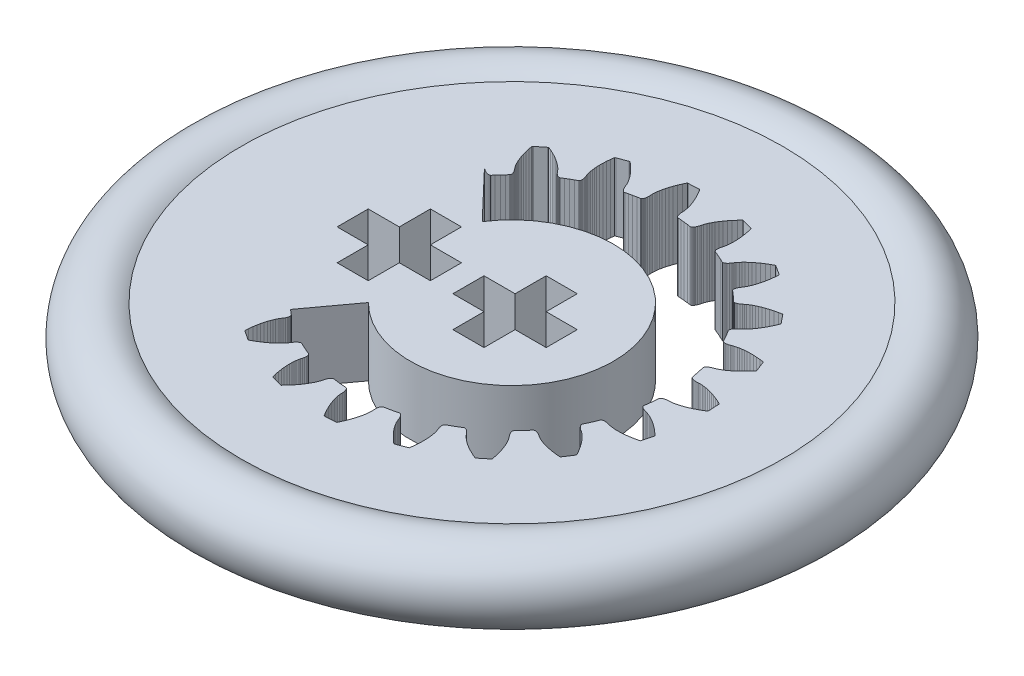
SolidWorks part; units mm, degrees
ref_plane "Front Plane" through (0, 0, 0) normal (0, 0, 1) x (1, 0, 0)
ref_plane "Top Plane" through (0, 0, 0) normal (0, 1, 0) x (1, 0, 0)
ref_plane "Right Plane" through (0, 0, 0) normal (1, 0, 0) x (0, 0, -1)
sketch "Sketch1" plane through (0, 0, 0) normal (0, 0, 1) x (1, 0, 0)
  line L0 (0, 0) -> (-11.938, 0)
  line L1 (-11.0639, 2.7724) -> (0, 2.7724)
  line L2 (0, 2.7724) -> (0, 0)
  line L3 (-11.938, 1.524) -> (-11.938, 3.048) construction
  line L4 (-11.938, 1.524) -> (-11.0639, 2.7724) construction
  arc A0 (-11.938, 0) -> (-11.0639, 2.7724) centre (-11.938, 1.524) cw
  dimension "D1" = 1.524
  dimension ".94/2" = 11.938
  dimension "D3" = 35
revolve "Revolve1" add sketch "Sketch1" angle 360 about L2
sketch "Sketch2" plane through (0, 2.7724, 0) normal (0, 1, 0) x (1, 0, 0)
  line L0 (-2.9392, -2.9262) -> (-4.2846, -4.7586)
  line L1 (-3.4764, 2.2619) -> (-5.3211, 4.1958)
  line L684 (7.7125, 0.0884) -> (7.5777, 0.013)
  line L685 (7.5777, 0.013) -> (7.4507, -0.0512)
  line L686 (7.4507, -0.0512) -> (7.332, -0.1049)
  line L687 (7.332, -0.1049) -> (7.2218, -0.1493)
  line L688 (7.2218, -0.1493) -> (7.1202, -0.1856)
  line L689 (7.1202, -0.1856) -> (7.0292, -0.2135)
  line L690 (7.0292, -0.2135) -> (6.9484, -0.235)
  line L691 (6.9484, -0.235) -> (6.8784, -0.2501)
  line L692 (6.8784, -0.2501) -> (6.7713, -0.2671)
  line L693 (6.7713, -0.2671) -> (6.7097, -0.2717)
  line L694 (6.7097, -0.2717) -> (6.6537, -0.2735)
  line L695 (6.6537, -0.2735) -> (6.5775, -0.2818)
  line L696 (6.5775, -0.2818) -> (6.5137, -0.2964)
  line L697 (6.5137, -0.2964) -> (6.4868, -0.3059)
  line L698 (6.4868, -0.3059) -> (6.4632, -0.3168)
  line L699 (6.4632, -0.3168) -> (6.4425, -0.3284)
  line L700 (6.4425, -0.3284) -> (6.4255, -0.341)
  line L701 (6.4255, -0.341) -> (6.4115, -0.354)
  line L702 (6.4115, -0.354) -> (6.4013, -0.3684)
  line L703 (6.4013, -0.3684) -> (6.3942, -0.383)
  line L704 (6.3942, -0.383) -> (6.3904, -0.4019)
  line L705 (6.3904, -0.4019) -> (6.3821, -0.5191)
  line L706 (6.3821, -0.5191) -> (6.3678, -0.6695)
  line L707 (6.3678, -0.6695) -> (6.3504, -0.8194)
  line L708 (6.3504, -0.8194) -> (6.3343, -0.9361)
  line L709 (6.3343, -0.9361) -> (6.334, -0.9552)
  line L710 (6.334, -0.9552) -> (6.3379, -0.9706)
  line L711 (6.3379, -0.9706) -> (6.3451, -0.9869)
  line L712 (6.3451, -0.9869) -> (6.356, -1.0026)
  line L713 (6.356, -1.0026) -> (6.37, -1.0187)
  line L714 (6.37, -1.0187) -> (6.3875, -1.0342)
  line L715 (6.3875, -1.0342) -> (6.4086, -1.0495)
  line L716 (6.4086, -1.0495) -> (6.433, -1.0644)
  line L717 (6.433, -1.0644) -> (6.4922, -1.0923)
  line L718 (6.4922, -1.0923) -> (6.5653, -1.1162)
  line L719 (6.5653, -1.1162) -> (6.6196, -1.1296)
  line L720 (6.6196, -1.1296) -> (6.6786, -1.1466)
  line L721 (6.6786, -1.1466) -> (6.7801, -1.1854)
  line L722 (6.7801, -1.1854) -> (6.8453, -1.2149)
  line L723 (6.8453, -1.2149) -> (6.9202, -1.2529)
  line L724 (6.9202, -1.2529) -> (7.0032, -1.2991)
  line L725 (7.0032, -1.2991) -> (7.0951, -1.3557)
  line L726 (7.0951, -1.3557) -> (7.1936, -1.422)
  line L727 (7.1936, -1.422) -> (7.2987, -1.4993)
  line L728 (7.2987, -1.4993) -> (7.4094, -1.5885)
  line L729 (7.4094, -1.5885) -> (7.5257, -1.6899)
  line L730 (7.5257, -1.6899) -> (7.6352, -1.794)
  line L731 (7.6352, -1.794) -> (7.6257, -1.8334)
  line L732 (7.6257, -1.8334) -> (7.5208, -2.2251)
  line L733 (7.5208, -2.2251) -> (7.5092, -2.2644)
  line L734 (7.5092, -2.2644) -> (7.3624, -2.2993)
  line L735 (7.3624, -2.2993) -> (7.2109, -2.3294)
  line L736 (7.2109, -2.3294) -> (7.0705, -2.3509)
  line L737 (7.0705, -2.3509) -> (6.9408, -2.3657)
  line L738 (6.9408, -2.3657) -> (6.8223, -2.3739)
  line L739 (6.8223, -2.3739) -> (6.7145, -2.3766)
  line L740 (6.7145, -2.3766) -> (6.6194, -2.3755)
  line L741 (6.6194, -2.3755) -> (6.5356, -2.3706)
  line L742 (6.5356, -2.3706) -> (6.4644, -2.3635)
  line L743 (6.4644, -2.3635) -> (6.3571, -2.3464)
  line L744 (6.3571, -2.3464) -> (6.2975, -2.3319)
  line L745 (6.2975, -2.3319) -> (6.2437, -2.3163)
  line L746 (6.2437, -2.3163) -> (6.1684, -2.3006)
  line L747 (6.1684, -2.3006) -> (6.1033, -2.2947)
  line L748 (6.1033, -2.2947) -> (6.0747, -2.2954)
  line L749 (6.0747, -2.2954) -> (6.0488, -2.2981)
  line L750 (6.0488, -2.2981) -> (6.0259, -2.3031)
  line L751 (6.0259, -2.3031) -> (6.0058, -2.3097)
  line L752 (6.0058, -2.3097) -> (5.9883, -2.3182)
  line L753 (5.9883, -2.3182) -> (5.9741, -2.3284)
  line L754 (5.9741, -2.3284) -> (5.9629, -2.3402)
  line L755 (5.9629, -2.3402) -> (5.9536, -2.3568)
  line L756 (5.9536, -2.3568) -> (5.9092, -2.466)
  line L757 (5.9092, -2.466) -> (5.8493, -2.6045)
  line L758 (5.8493, -2.6045) -> (5.7866, -2.7415)
  line L759 (5.7866, -2.7415) -> (5.735, -2.8476)
  line L760 (5.735, -2.8476) -> (5.729, -2.8659)
  line L761 (5.729, -2.8659) -> (5.7278, -2.8819)
  line L762 (5.7278, -2.8819) -> (5.7295, -2.8992)
  line L763 (5.7295, -2.8992) -> (5.735, -2.9178)
  line L764 (5.735, -2.9178) -> (5.7434, -2.9373)
  line L765 (5.7434, -2.9373) -> (5.7555, -2.9577)
  line L766 (5.7555, -2.9577) -> (5.7707, -2.9785)
  line L767 (5.7707, -2.9785) -> (5.7892, -3.0003)
  line L768 (5.7892, -3.0003) -> (5.8371, -3.0451)
  line L769 (5.8371, -3.0451) -> (5.8989, -3.0904)
  line L770 (5.8989, -3.0904) -> (5.9465, -3.1199)
  line L771 (5.9465, -3.1199) -> (5.9976, -3.1544)
  line L772 (5.9976, -3.1544) -> (6.0819, -3.2225)
  line L773 (6.0819, -3.2225) -> (6.1349, -3.2711)
  line L774 (6.1349, -3.2711) -> (6.1942, -3.3297)
  line L775 (6.1942, -3.3297) -> (6.259, -3.3998)
  line L776 (6.259, -3.3998) -> (6.3289, -3.4816)
  line L777 (6.3289, -3.4816) -> (6.4021, -3.5751)
  line L778 (6.4021, -3.5751) -> (6.478, -3.6814)
  line L779 (6.478, -3.6814) -> (6.5559, -3.8005)
  line L780 (6.5559, -3.8005) -> (6.6351, -3.9328)
  line L781 (6.6351, -3.9328) -> (6.707, -4.0655)
  line L782 (6.707, -4.0655) -> (6.6857, -4.1001)
  line L783 (6.6857, -4.1001) -> (6.4647, -4.4404)
  line L784 (6.4647, -4.4404) -> (6.4417, -4.4738)
  line L785 (6.4417, -4.4738) -> (6.2915, -4.4619)
  line L786 (6.2915, -4.4619) -> (6.1382, -4.4436)
  line L787 (6.1382, -4.4436) -> (5.9978, -4.4207)
  line L788 (5.9978, -4.4207) -> (5.8699, -4.3944)
  line L789 (5.8699, -4.3944) -> (5.7548, -4.366)
  line L790 (5.7548, -4.366) -> (5.6515, -4.3355)
  line L791 (5.6515, -4.3355) -> (5.5612, -4.3045)
  line L792 (5.5612, -4.3045) -> (5.4834, -4.2745)
  line L793 (5.4834, -4.2745) -> (5.4176, -4.2457)
  line L794 (5.4176, -4.2457) -> (5.3209, -4.1962)
  line L795 (5.3209, -4.1962) -> (5.2685, -4.1638)
  line L796 (5.2685, -4.1638) -> (5.2223, -4.1322)
  line L797 (5.2223, -4.1322) -> (5.1558, -4.094)
  line L798 (5.1558, -4.094) -> (5.0955, -4.0687)
  line L799 (5.0955, -4.0687) -> (5.0682, -4.0606)
  line L800 (5.0682, -4.0606) -> (5.0428, -4.055)
  line L801 (5.0428, -4.055) -> (5.0192, -4.0522)
  line L802 (5.0192, -4.0522) -> (4.998, -4.0526)
  line L803 (4.998, -4.0526) -> (4.9788, -4.0554)
  line L804 (4.9788, -4.0554) -> (4.9623, -4.0606)
  line L805 (4.9623, -4.0606) -> (4.9481, -4.0684)
  line L806 (4.9481, -4.0684) -> (4.9339, -4.0813)
  line L807 (4.9339, -4.0813) -> (4.8579, -4.1712)
  line L808 (4.8579, -4.1712) -> (4.7583, -4.2847)
  line L809 (4.7583, -4.2847) -> (4.6559, -4.3955)
  line L810 (4.6559, -4.3955) -> (4.5745, -4.4803)
  line L811 (4.5745, -4.4803) -> (4.5631, -4.4961)
  line L812 (4.5631, -4.4961) -> (4.5568, -4.5108)
  line L813 (4.5568, -4.5108) -> (4.5534, -4.5278)
  line L814 (4.5534, -4.5278) -> (4.5526, -4.5472)
  line L815 (4.5526, -4.5472) -> (4.5545, -4.5685)
  line L816 (4.5545, -4.5685) -> (4.5596, -4.5914)
  line L817 (4.5596, -4.5914) -> (4.5678, -4.616)
  line L818 (4.5678, -4.616) -> (4.579, -4.6425)
  line L819 (4.579, -4.6425) -> (4.6104, -4.6997)
  line L820 (4.6104, -4.6997) -> (4.6552, -4.762)
  line L821 (4.6552, -4.762) -> (4.6914, -4.8045)
  line L822 (4.6914, -4.8045) -> (4.729, -4.8533)
  line L823 (4.729, -4.8533) -> (4.7882, -4.9442)
  line L824 (4.7882, -4.9442) -> (4.8239, -5.0066)
  line L825 (4.8239, -5.0066) -> (4.8621, -5.0811)
  line L826 (4.8621, -5.0811) -> (4.902, -5.1677)
  line L827 (4.902, -5.1677) -> (4.9433, -5.267)
  line L828 (4.9433, -5.267) -> (4.9838, -5.3786)
  line L829 (4.9838, -5.3786) -> (5.0235, -5.503)
  line L830 (5.0235, -5.503) -> (5.0606, -5.6404)
  line L831 (5.0606, -5.6404) -> (5.095, -5.791)
  line L832 (5.095, -5.791) -> (5.1228, -5.9391)
  line L833 (5.1228, -5.9391) -> (5.0917, -5.9655)
  line L834 (5.0917, -5.9655) -> (4.7764, -6.221)
  line L835 (4.7764, -6.221) -> (4.7442, -6.2455)
  line L836 (4.7442, -6.2455) -> (4.6048, -6.1878)
  line L837 (4.6048, -6.1878) -> (4.4648, -6.1231)
  line L838 (4.4648, -6.1231) -> (4.3379, -6.058)
  line L839 (4.3379, -6.058) -> (4.2246, -5.9932)
  line L840 (4.2246, -5.9932) -> (4.1241, -5.9304)
  line L841 (4.1241, -5.9304) -> (4.0352, -5.8698)
  line L842 (4.0352, -5.8698) -> (3.9587, -5.8125)
  line L843 (3.9587, -5.8125) -> (3.8941, -5.7597)
  line L844 (3.8941, -5.7597) -> (3.8403, -5.7117)
  line L845 (3.8403, -5.7117) -> (3.7639, -5.6349)
  line L846 (3.7639, -5.6349) -> (3.724, -5.5883)
  line L847 (3.724, -5.5883) -> (3.6899, -5.544)
  line L848 (3.6899, -5.544) -> (3.6381, -5.487)
  line L849 (3.6381, -5.487) -> (3.5889, -5.4442)
  line L850 (3.5889, -5.4442) -> (3.5652, -5.4279)
  line L851 (3.5652, -5.4279) -> (3.5429, -5.4147)
  line L852 (3.5429, -5.4147) -> (3.5214, -5.4053)
  line L853 (3.5214, -5.4053) -> (3.5011, -5.3987)
  line L854 (3.5011, -5.3987) -> (3.482, -5.3956)
  line L855 (3.482, -5.3956) -> (3.4645, -5.3953)
  line L856 (3.4645, -5.3953) -> (3.4486, -5.3982)
  line L857 (3.4486, -5.3982) -> (3.4312, -5.4063)
  line L858 (3.4312, -5.4063) -> (3.3311, -5.4682)
  line L859 (3.3311, -5.4682) -> (3.2014, -5.5453)
  line L860 (3.2014, -5.5453) -> (3.0699, -5.6191)
  line L861 (3.0699, -5.6191) -> (2.9662, -5.6748)
  line L862 (2.9662, -5.6748) -> (2.9504, -5.6858)
  line L863 (2.9504, -5.6858) -> (2.94, -5.6981)
  line L864 (2.94, -5.6981) -> (2.9314, -5.7134)
  line L865 (2.9314, -5.7134) -> (2.9247, -5.7316)
  line L866 (2.9247, -5.7316) -> (2.9202, -5.7524)
  line L867 (2.9202, -5.7524) -> (2.9176, -5.7757)
  line L868 (2.9176, -5.7757) -> (2.9178, -5.8017)
  line L869 (2.9178, -5.8017) -> (2.9202, -5.8303)
  line L870 (2.9202, -5.8303) -> (2.9326, -5.8943)
  line L871 (2.9326, -5.8943) -> (2.956, -5.9677)
  line L872 (2.956, -5.9677) -> (2.9774, -6.0194)
  line L873 (2.9774, -6.0194) -> (2.9978, -6.0772)
  line L874 (2.9978, -6.0772) -> (3.0262, -6.1818)
  line L875 (3.0262, -6.1818) -> (3.0407, -6.2524)
  line L876 (3.0407, -6.2524) -> (3.0542, -6.3347)
  line L877 (3.0542, -6.3347) -> (3.0656, -6.4297)
  line L878 (3.0656, -6.4297) -> (3.0736, -6.5369)
  line L879 (3.0736, -6.5369) -> (3.0778, -6.6554)
  line L880 (3.0778, -6.6554) -> (3.0772, -6.7859)
  line L881 (3.0772, -6.7859) -> (3.0702, -6.9282)
  line L882 (3.0702, -6.9282) -> (3.0562, -7.0819)
  line L883 (3.0562, -7.0819) -> (3.0364, -7.2316)
  line L884 (3.0364, -7.2316) -> (2.9991, -7.2471)
  line L885 (2.9991, -7.2471) -> (2.6203, -7.3925)
  line L886 (2.6203, -7.3925) -> (2.5818, -7.4061)
  line L887 (2.5818, -7.4061) -> (2.4675, -7.308)
  line L888 (2.4675, -7.308) -> (2.3542, -7.203)
  line L889 (2.3542, -7.203) -> (2.2538, -7.1021)
  line L890 (2.2538, -7.1021) -> (2.1659, -7.0055)
  line L891 (2.1659, -7.0055) -> (2.0895, -6.9147)
  line L892 (2.0895, -6.9147) -> (2.0241, -6.8293)
  line L893 (2.0241, -6.8293) -> (1.9691, -6.7514)
  line L894 (1.9691, -6.7514) -> (1.9237, -6.6809)
  line L895 (1.9237, -6.6809) -> (1.8875, -6.6189)
  line L896 (1.8875, -6.6189) -> (1.8384, -6.5223)
  line L897 (1.8384, -6.5223) -> (1.8149, -6.4652)
  line L898 (1.8149, -6.4652) -> (1.7962, -6.4127)
  line L899 (1.7962, -6.4127) -> (1.7646, -6.3427)
  line L900 (1.7646, -6.3427) -> (1.7308, -6.2869)
  line L901 (1.7308, -6.2869) -> (1.7134, -6.2639)
  line L902 (1.7134, -6.2639) -> (1.6963, -6.2445)
  line L903 (1.6963, -6.2445) -> (1.6789, -6.2287)
  line L904 (1.6789, -6.2287) -> (1.6615, -6.2164)
  line L905 (1.6615, -6.2164) -> (1.6443, -6.2074)
  line L906 (1.6443, -6.2074) -> (1.6278, -6.2018)
  line L907 (1.6278, -6.2018) -> (1.6119, -6.1999)
  line L908 (1.6119, -6.1999) -> (1.5927, -6.202)
  line L909 (1.5927, -6.202) -> (1.4784, -6.2301)
  line L910 (1.4784, -6.2301) -> (1.3312, -6.2634)
  line L911 (1.3312, -6.2634) -> (1.1832, -6.2928)
  line L912 (1.1832, -6.2928) -> (1.0673, -6.3137)
  line L913 (1.0673, -6.3137) -> (1.049, -6.3195)
  line L914 (1.049, -6.3195) -> (1.0352, -6.3278)
  line L915 (1.0352, -6.3278) -> (1.0225, -6.3396)
  line L916 (1.0225, -6.3396) -> (1.0104, -6.3547)
  line L917 (1.0104, -6.3547) -> (0.9995, -6.373)
  line L918 (0.9995, -6.373) -> (0.9901, -6.3948)
  line L919 (0.9901, -6.3948) -> (0.9822, -6.4195)
  line L920 (0.9822, -6.4195) -> (0.9756, -6.4473)
  line L921 (0.9756, -6.4473) -> (0.9674, -6.5122)
  line L922 (0.9674, -6.5122) -> (0.9673, -6.5888)
  line L923 (0.9673, -6.5888) -> (0.9715, -6.6447)
  line L924 (0.9715, -6.6447) -> (0.9733, -6.7063)
  line L925 (0.9733, -6.7063) -> (0.9679, -6.8147)
  line L926 (0.9679, -6.8147) -> (0.9599, -6.8861)
  line L927 (0.9599, -6.8861) -> (0.947, -6.9685)
  line L928 (0.947, -6.9685) -> (0.9286, -7.0623)
  line L929 (0.9286, -7.0623) -> (0.9034, -7.1669)
  line L930 (0.9034, -7.1669) -> (0.8705, -7.2808)
  line L931 (0.8705, -7.2808) -> (0.8293, -7.4047)
  line L932 (0.8293, -7.4047) -> (0.7789, -7.5378)
  line L933 (0.7789, -7.5378) -> (0.7181, -7.6797)
  line L934 (0.7181, -7.6797) -> (0.6533, -7.8158)
  line L935 (0.6533, -7.8158) -> (0.6129, -7.8189)
  line L936 (0.6129, -7.8189) -> (0.2078, -7.8402)
  line L937 (0.2078, -7.8402) -> (0.1671, -7.8413)
  line L938 (0.1671, -7.8413) -> (0.0881, -7.7127)
  line L939 (0.0881, -7.7127) -> (0.0131, -7.5779)
  line L940 (0.0131, -7.5779) -> (-0.051, -7.4509)
  line L941 (-0.051, -7.4509) -> (-0.1051, -7.3321)
  line L942 (-0.1051, -7.3321) -> (-0.1495, -7.222)
  line L943 (-0.1495, -7.222) -> (-0.1854, -7.1204)
  line L944 (-0.1854, -7.1204) -> (-0.2137, -7.0294)
  line L945 (-0.2137, -7.0294) -> (-0.2348, -6.9486)
  line L946 (-0.2348, -6.9486) -> (-0.2504, -6.8785)
  line L947 (-0.2504, -6.8785) -> (-0.2673, -6.7714)
  line L948 (-0.2673, -6.7714) -> (-0.2716, -6.7099)
  line L949 (-0.2716, -6.7099) -> (-0.2734, -6.6539)
  line L950 (-0.2734, -6.6539) -> (-0.2817, -6.5778)
  line L951 (-0.2817, -6.5778) -> (-0.2966, -6.5138)
  line L952 (-0.2966, -6.5138) -> (-0.3062, -6.4869)
  line L953 (-0.3062, -6.4869) -> (-0.3166, -6.4634)
  line L954 (-0.3166, -6.4634) -> (-0.3282, -6.4426)
  line L955 (-0.3282, -6.4426) -> (-0.3408, -6.4257)
  line L956 (-0.3408, -6.4257) -> (-0.3543, -6.4117)
  line L957 (-0.3543, -6.4117) -> (-0.3683, -6.4016)
  line L958 (-0.3683, -6.4016) -> (-0.3828, -6.3945)
  line L959 (-0.3828, -6.3945) -> (-0.4017, -6.3906)
  line L960 (-0.4017, -6.3906) -> (-0.5193, -6.3823)
  line L961 (-0.5193, -6.3823) -> (-0.6693, -6.368)
  line L962 (-0.6693, -6.368) -> (-0.8192, -6.3506)
  line L963 (-0.8192, -6.3506) -> (-0.9359, -6.3345)
  line L964 (-0.9359, -6.3345) -> (-0.9551, -6.3342)
  line L965 (-0.9551, -6.3342) -> (-0.9708, -6.338)
  line L966 (-0.9708, -6.338) -> (-0.9868, -6.3453)
  line L967 (-0.9868, -6.3453) -> (-1.0028, -6.3562)
  line L968 (-1.0028, -6.3562) -> (-1.0186, -6.3703)
  line L969 (-1.0186, -6.3703) -> (-1.0345, -6.3876)
  line L970 (-1.0345, -6.3876) -> (-1.0497, -6.4087)
  line L971 (-1.0497, -6.4087) -> (-1.0646, -6.4331)
  line L972 (-1.0646, -6.4331) -> (-1.0921, -6.4924)
  line L973 (-1.0921, -6.4924) -> (-1.1161, -6.5655)
  line L974 (-1.1161, -6.5655) -> (-1.1295, -6.6198)
  line L975 (-1.1295, -6.6198) -> (-1.1468, -6.6787)
  line L976 (-1.1468, -6.6787) -> (-1.1856, -6.7802)
  line L977 (-1.1856, -6.7802) -> (-1.2151, -6.8454)
  line L978 (-1.2151, -6.8454) -> (-1.2527, -6.9204)
  line L979 (-1.2527, -6.9204) -> (-1.2993, -7.0034)
  line L980 (-1.2993, -7.0034) -> (-1.3555, -7.0953)
  line L981 (-1.3555, -7.0953) -> (-1.4218, -7.1938)
  line L982 (-1.4218, -7.1938) -> (-1.4995, -7.2988)
  line L983 (-1.4995, -7.2988) -> (-1.5883, -7.4097)
  line L984 (-1.5883, -7.4097) -> (-1.6901, -7.5258)
  line L985 (-1.6901, -7.5258) -> (-1.7939, -7.6354)
  line L986 (-1.7939, -7.6354) -> (-1.8337, -7.6259)
  line L987 (-1.8337, -7.6259) -> (-2.2254, -7.521)
  line L988 (-2.2254, -7.521) -> (-2.2642, -7.5094)
  line L989 (-2.2642, -7.5094) -> (-2.2995, -7.3625)
  line L990 (-2.2995, -7.3625) -> (-2.3293, -7.2111)
  line L991 (-2.3293, -7.2111) -> (-2.3511, -7.0706)
  line L992 (-2.3511, -7.0706) -> (-2.3655, -6.941)
  line L993 (-2.3655, -6.941) -> (-2.3738, -6.8225)
  line L994 (-2.3738, -6.8225) -> (-2.3768, -6.7146)
  line L995 (-2.3768, -6.7146) -> (-2.3753, -6.6196)
  line L996 (-2.3753, -6.6196) -> (-2.3708, -6.5357)
  line L997 (-2.3708, -6.5357) -> (-2.3637, -6.4645)
  line L998 (-2.3637, -6.4645) -> (-2.3466, -6.3572)
  line L999 (-2.3466, -6.3572) -> (-2.3318, -6.2977)
  line L1000 (-2.3318, -6.2977) -> (-2.3162, -6.2439)
  line L1001 (-2.3162, -6.2439) -> (-2.3004, -6.1687)
  line L1002 (-2.3004, -6.1687) -> (-2.2949, -6.1034)
  line L1003 (-2.2949, -6.1034) -> (-2.2956, -6.0749)
  line L1004 (-2.2956, -6.0749) -> (-2.2983, -6.049)
  line L1005 (-2.2983, -6.049) -> (-2.303, -6.0262)
  line L1006 (-2.303, -6.0262) -> (-2.3099, -6.0059)
  line L1007 (-2.3099, -6.0059) -> (-2.3181, -5.9886)
  line L1008 (-2.3181, -5.9886) -> (-2.3286, -5.9742)
  line L1009 (-2.3286, -5.9742) -> (-2.34, -5.9631)
  line L1010 (-2.34, -5.9631) -> (-2.3567, -5.9539)
  line L1011 (-2.3567, -5.9539) -> (-2.4658, -5.9094)
  line L1012 (-2.4658, -5.9094) -> (-2.6044, -5.8495)
  line L1013 (-2.6044, -5.8495) -> (-2.7417, -5.7868)
  line L1014 (-2.7417, -5.7868) -> (-2.8474, -5.7353)
  line L1015 (-2.8474, -5.7353) -> (-2.8657, -5.7292)
  line L1016 (-2.8657, -5.7292) -> (-2.8818, -5.7281)
  line L1017 (-2.8818, -5.7281) -> (-2.8994, -5.7297)
  line L1018 (-2.8994, -5.7297) -> (-2.9177, -5.7352)
  line L1019 (-2.9177, -5.7352) -> (-2.9371, -5.7436)
  line L1020 (-2.9371, -5.7436) -> (-2.9575, -5.7557)
  line L1021 (-2.9575, -5.7557) -> (-2.9787, -5.7708)
  line L1022 (-2.9787, -5.7708) -> (-3.0005, -5.7893)
  line L1023 (-3.0005, -5.7893) -> (-3.0449, -5.8374)
  line L1024 (-3.0449, -5.8374) -> (-3.0902, -5.8991)
  line L1025 (-3.0902, -5.8991) -> (-3.1197, -5.9467)
  line L1026 (-3.1197, -5.9467) -> (-3.1546, -5.9977)
  line L1027 (-3.1546, -5.9977) -> (-3.2227, -6.0821)
  line L1028 (-3.2227, -6.0821) -> (-3.2709, -6.1351)
  line L1029 (-3.2709, -6.1351) -> (-3.3299, -6.1944)
  line L1030 (-3.3299, -6.1944) -> (-3.3996, -6.2592)
  line L1031 (-3.3996, -6.2592) -> (-3.4819, -6.3291)
  line L1032 (-3.4819, -6.3291) -> (-3.5753, -6.4023)
  line L1033 (-3.5753, -6.4023) -> (-3.6812, -6.4782)
  line L1034 (-3.6812, -6.4782) -> (-3.8003, -6.5561)
  line L1035 (-3.8003, -6.5561) -> (-3.933, -6.6352)
  line L1036 (-3.933, -6.6352) -> (-4.0653, -6.7072)
  line L1037 (-4.0653, -6.7072) -> (-4.1, -6.6859)
  line L1038 (-4.1, -6.6859) -> (-4.4406, -6.4648)
  line L1039 (-4.4406, -6.4648) -> (-4.474, -6.4419)
  line L1040 (-4.474, -6.4419) -> (-4.4621, -6.2917)
  line L1041 (-4.4621, -6.2917) -> (-4.4438, -6.1384)
  line L1042 (-4.4438, -6.1384) -> (-4.4209, -5.9979)
  line L1043 (-4.4209, -5.9979) -> (-4.3946, -5.87)
  line L1044 (-4.3946, -5.87) -> (-4.3659, -5.755)
  line L1045 (-4.3659, -5.755) -> (-4.3354, -5.6518)
  line L1046 (-4.3354, -5.6518) -> (-4.3047, -5.5613)
  line L1047 (-4.3047, -5.5613) -> (-4.2743, -5.4836)
  line L1048 (-4.2743, -5.4836) -> (-4.2455, -5.4178)
  line L1049 (-4.2455, -5.4178) -> (-4.1961, -5.3212)
  line L1050 (-4.1961, -5.3212) -> (-4.1636, -5.2688)
  line L1051 (-4.1636, -5.2688) -> (-4.1321, -5.2225)
  line L1052 (-4.1321, -5.2225) -> (-4.0943, -5.1559)
  line L1053 (-4.0943, -5.1559) -> (-4.0685, -5.0957)
  line L1054 (-4.0685, -5.0957) -> (-4.0604, -5.0683)
  line L1055 (-4.0604, -5.0683) -> (-4.0552, -5.043)
  line L1056 (-4.0552, -5.043) -> (-4.0525, -5.0193)
  line L1057 (-4.0525, -5.0193) -> (-4.0528, -4.9981)
  line L1058 (-4.0528, -4.9981) -> (-4.0553, -4.979)
  line L1059 (-4.0553, -4.979) -> (-4.0608, -4.9624)
  line L1060 (-4.0608, -4.9624) -> (-4.0682, -4.9484)
  line L1061 (-4.0682, -4.9484) -> (-4.0812, -4.9341)
  line L1062 (-4.0812, -4.9341) -> (-4.1714, -4.858)
  line L1063 (-4.1714, -4.858) -> (-4.2846, -4.7586)
  line L1305 (-5.3211, 4.1958) -> (-5.269, 4.1635)
  line L1306 (-5.269, 4.1635) -> (-5.2227, 4.1319)
  line L1307 (-5.2227, 4.1319) -> (-5.1558, 4.094)
  line L1308 (-5.1558, 4.094) -> (-5.0959, 4.0684)
  line L1309 (-5.0959, 4.0684) -> (-5.0682, 4.0602)
  line L1310 (-5.0682, 4.0602) -> (-5.0428, 4.055)
  line L1311 (-5.0428, 4.055) -> (-5.0196, 4.0524)
  line L1312 (-5.0196, 4.0524) -> (-4.9983, 4.0527)
  line L1313 (-4.9983, 4.0527) -> (-4.9793, 4.0551)
  line L1314 (-4.9793, 4.0551) -> (-4.9626, 4.0607)
  line L1315 (-4.9626, 4.0607) -> (-4.9482, 4.068)
  line L1316 (-4.9482, 4.068) -> (-4.934, 4.081)
  line L1317 (-4.934, 4.081) -> (-4.8583, 4.1713)
  line L1318 (-4.8583, 4.1713) -> (-4.7584, 4.2843)
  line L1319 (-4.7584, 4.2843) -> (-4.6564, 4.3953)
  line L1320 (-4.6564, 4.3953) -> (-4.5745, 4.4804)
  line L1321 (-4.5745, 4.4804) -> (-4.5632, 4.4957)
  line L1322 (-4.5632, 4.4957) -> (-4.5572, 4.5108)
  line L1323 (-4.5572, 4.5108) -> (-4.5534, 4.5278)
  line L1324 (-4.5534, 4.5278) -> (-4.5527, 4.5468)
  line L1325 (-4.5527, 4.5468) -> (-4.555, 4.5682)
  line L1326 (-4.555, 4.5682) -> (-4.56, 4.5911)
  line L1327 (-4.56, 4.5911) -> (-4.5681, 4.616)
  line L1328 (-4.5681, 4.616) -> (-4.579, 4.6425)
  line L1329 (-4.579, 4.6425) -> (-4.6108, 4.6997)
  line L1330 (-4.6108, 4.6997) -> (-4.6557, 4.7618)
  line L1331 (-4.6557, 4.7618) -> (-4.6918, 4.8046)
  line L1332 (-4.6918, 4.8046) -> (-4.7295, 4.853)
  line L1333 (-4.7295, 4.853) -> (-4.7886, 4.944)
  line L1334 (-4.7886, 4.944) -> (-4.8242, 5.0067)
  line L1335 (-4.8242, 5.0067) -> (-4.8622, 5.0808)
  line L1336 (-4.8622, 5.0808) -> (-4.9025, 5.1675)
  line L1337 (-4.9025, 5.1675) -> (-4.9433, 5.2671)
  line L1338 (-4.9433, 5.2671) -> (-4.9841, 5.3787)
  line L1339 (-4.9841, 5.3787) -> (-5.0236, 5.5027)
  line L1340 (-5.0236, 5.5027) -> (-5.0611, 5.6402)
  line L1341 (-5.0611, 5.6402) -> (-5.0954, 5.7907)
  line L1342 (-5.0954, 5.7907) -> (-5.1228, 5.9391)
  line L1343 (-5.1228, 5.9391) -> (-5.0921, 5.9657)
  line L1344 (-5.0921, 5.9657) -> (-4.7768, 6.2211)
  line L1345 (-4.7768, 6.2211) -> (-4.7443, 6.2455)
  line L1346 (-4.7443, 6.2455) -> (-4.6051, 6.1879)
  line L1347 (-4.6051, 6.1879) -> (-4.4648, 6.1227)
  line L1348 (-4.4648, 6.1227) -> (-4.3384, 6.0577)
  line L1349 (-4.3384, 6.0577) -> (-4.225, 5.9934)
  line L1350 (-4.225, 5.9934) -> (-4.1241, 5.9303)
  line L1351 (-4.1241, 5.9303) -> (-4.0353, 5.8695)
  line L1352 (-4.0353, 5.8695) -> (-3.9592, 5.8122)
  line L1353 (-3.9592, 5.8122) -> (-3.8943, 5.7594)
  line L1354 (-3.8943, 5.7594) -> (-3.8407, 5.7119)
  line L1355 (-3.8407, 5.7119) -> (-3.7642, 5.635)
  line L1356 (-3.7642, 5.635) -> (-3.7241, 5.5879)
  line L1357 (-3.7241, 5.5879) -> (-3.69, 5.5437)
  line L1358 (-3.69, 5.5437) -> (-3.6385, 5.4871)
  line L1359 (-3.6385, 5.4871) -> (-3.5893, 5.4439)
  line L1360 (-3.5893, 5.4439) -> (-3.5657, 5.4276)
  line L1361 (-3.5657, 5.4276) -> (-3.5432, 5.4148)
  line L1362 (-3.5432, 5.4148) -> (-3.5215, 5.4049)
  line L1363 (-3.5215, 5.4049) -> (-3.5012, 5.3984)
  line L1364 (-3.5012, 5.3984) -> (-3.4825, 5.3953)
  line L1365 (-3.4825, 5.3953) -> (-3.465, 5.395)
  line L1366 (-3.465, 5.395) -> (-3.4489, 5.3982)
  line L1367 (-3.4489, 5.3982) -> (-3.4313, 5.406)
  line L1368 (-3.4313, 5.406) -> (-3.3315, 5.4684)
  line L1369 (-3.3315, 5.4684) -> (-3.2018, 5.5454)
  line L1370 (-3.2018, 5.5454) -> (-3.0702, 5.6192)
  line L1371 (-3.0702, 5.6192) -> (-2.9663, 5.6744)
  line L1372 (-2.9663, 5.6744) -> (-2.9508, 5.6859)
  line L1373 (-2.9508, 5.6859) -> (-2.94, 5.6982)
  line L1374 (-2.94, 5.6982) -> (-2.9315, 5.7134)
  line L1375 (-2.9315, 5.7134) -> (-2.9247, 5.7312)
  line L1376 (-2.9247, 5.7312) -> (-2.9203, 5.752)
  line L1377 (-2.9203, 5.752) -> (-2.918, 5.7757)
  line L1378 (-2.918, 5.7757) -> (-2.9178, 5.8017)
  line L1379 (-2.9178, 5.8017) -> (-2.9201, 5.8303)
  line L1380 (-2.9201, 5.8303) -> (-2.9329, 5.8944)
  line L1381 (-2.9329, 5.8944) -> (-2.9561, 5.9673)
  line L1382 (-2.9561, 5.9673) -> (-2.9774, 6.0189)
  line L1383 (-2.9774, 6.0189) -> (-2.9982, 6.0773)
  line L1384 (-2.9982, 6.0773) -> (-3.0264, 6.1819)
  line L1385 (-3.0264, 6.1819) -> (-3.0408, 6.252)
  line L1386 (-3.0408, 6.252) -> (-3.0542, 6.3348)
  line L1387 (-3.0542, 6.3348) -> (-3.0656, 6.4293)
  line L1388 (-3.0656, 6.4293) -> (-3.074, 6.5366)
  line L1389 (-3.074, 6.5366) -> (-3.0781, 6.6556)
  line L1390 (-3.0781, 6.6556) -> (-3.0771, 6.7858)
  line L1391 (-3.0771, 6.7858) -> (-3.0702, 6.9279)
  line L1392 (-3.0702, 6.9279) -> (-3.0565, 7.082)
  line L1393 (-3.0565, 7.082) -> (-3.0369, 7.2313)
  line L1394 (-3.0369, 7.2313) -> (-2.9994, 7.2472)
  line L1395 (-2.9994, 7.2472) -> (-2.6206, 7.3926)
  line L1396 (-2.6206, 7.3926) -> (-2.5822, 7.4059)
  line L1397 (-2.5822, 7.4059) -> (-2.4675, 7.308)
  line L1398 (-2.4675, 7.308) -> (-2.3542, 7.203)
  line L1399 (-2.3542, 7.203) -> (-2.2539, 7.1018)
  line L1400 (-2.2539, 7.1018) -> (-2.1662, 7.0056)
  line L1401 (-2.1662, 7.0056) -> (-2.09, 6.9144)
  line L1402 (-2.09, 6.9144) -> (-2.0241, 6.8293)
  line L1403 (-2.0241, 6.8293) -> (-1.9692, 6.7511)
  line L1404 (-1.9692, 6.7511) -> (-1.924, 6.6811)
  line L1405 (-1.924, 6.6811) -> (-1.8875, 6.619)
  line L1406 (-1.8875, 6.619) -> (-1.8383, 6.5222)
  line L1407 (-1.8383, 6.5222) -> (-1.8152, 6.4653)
  line L1408 (-1.8152, 6.4653) -> (-1.7962, 6.4126)
  line L1409 (-1.7962, 6.4126) -> (-1.765, 6.3428)
  line L1410 (-1.765, 6.3428) -> (-1.7313, 6.2867)
  line L1411 (-1.7313, 6.2867) -> (-1.7138, 6.264)
  line L1412 (-1.7138, 6.264) -> (-1.6962, 6.2446)
  line L1413 (-1.6962, 6.2446) -> (-1.6789, 6.2287)
  line L1414 (-1.6789, 6.2287) -> (-1.6615, 6.216)
  line L1415 (-1.6615, 6.216) -> (-1.6447, 6.2071)
  line L1416 (-1.6447, 6.2071) -> (-1.6282, 6.2019)
  line L1417 (-1.6282, 6.2019) -> (-1.612, 6.1996)
  line L1418 (-1.612, 6.1996) -> (-1.5931, 6.2017)
  line L1419 (-1.5931, 6.2017) -> (-1.4784, 6.2301)
  line L1420 (-1.4784, 6.2301) -> (-1.3314, 6.2629)
  line L1421 (-1.3314, 6.2629) -> (-1.1836, 6.2929)
  line L1422 (-1.1836, 6.2929) -> (-1.0674, 6.3133)
  line L1423 (-1.0674, 6.3133) -> (-1.0491, 6.3191)
  line L1424 (-1.0491, 6.3191) -> (-1.0355, 6.328)
  line L1425 (-1.0355, 6.328) -> (-1.0224, 6.3396)
  line L1426 (-1.0224, 6.3396) -> (-1.0108, 6.3549)
  line L1427 (-1.0108, 6.3549) -> (-0.9999, 6.3731)
  line L1428 (-0.9999, 6.3731) -> (-0.9905, 6.3945)
  line L1429 (-0.9905, 6.3945) -> (-0.9824, 6.4191)
  line L1430 (-0.9824, 6.4191) -> (-0.9756, 6.4473)
  line L1431 (-0.9756, 6.4473) -> (-0.9679, 6.5119)
  line L1432 (-0.9679, 6.5119) -> (-0.9672, 6.5889)
  line L1433 (-0.9672, 6.5889) -> (-0.9714, 6.6447)
  line L1434 (-0.9714, 6.6447) -> (-0.9734, 6.706)
  line L1435 (-0.9734, 6.706) -> (-0.9679, 6.8143)
  line L1436 (-0.9679, 6.8143) -> (-0.96, 6.8857)
  line L1437 (-0.96, 6.8857) -> (-0.9474, 6.9686)
  line L1438 (-0.9474, 6.9686) -> (-0.9288, 7.0619)
  line L1439 (-0.9288, 7.0619) -> (-0.9035, 7.1666)
  line L1440 (-0.9035, 7.1666) -> (-0.8709, 7.2809)
  line L1441 (-0.8709, 7.2809) -> (-0.8298, 7.4045)
  line L1442 (-0.8298, 7.4045) -> (-0.7793, 7.5376)
  line L1443 (-0.7793, 7.5376) -> (-0.7185, 7.6798)
  line L1444 (-0.7185, 7.6798) -> (-0.6537, 7.8158)
  line L1445 (-0.6537, 7.8158) -> (-0.6131, 7.8194)
  line L1446 (-0.6131, 7.8194) -> (-0.2076, 7.8405)
  line L1447 (-0.2076, 7.8405) -> (-0.1671, 7.8413)
  line L1448 (-0.1671, 7.8413) -> (-0.0885, 7.7127)
  line L1449 (-0.0885, 7.7127) -> (-0.0131, 7.5779)
  line L1450 (-0.0131, 7.5779) -> (0.0511, 7.4509)
  line L1451 (0.0511, 7.4509) -> (0.1047, 7.3318)
  line L1452 (0.1047, 7.3318) -> (0.149, 7.2217)
  line L1453 (0.149, 7.2217) -> (0.1855, 7.1205)
  line L1454 (0.1855, 7.1205) -> (0.2133, 7.0291)
  line L1455 (0.2133, 7.0291) -> (0.2348, 6.9482)
  line L1456 (0.2348, 6.9482) -> (0.25, 6.8783)
  line L1457 (0.25, 6.8783) -> (0.2668, 6.7712)
  line L1458 (0.2668, 6.7712) -> (0.2716, 6.71)
  line L1459 (0.2716, 6.71) -> (0.2734, 6.6539)
  line L1460 (0.2734, 6.6539) -> (0.2816, 6.5774)
  line L1461 (0.2816, 6.5774) -> (0.2962, 6.5139)
  line L1462 (0.2962, 6.5139) -> (0.3056, 6.4866)
  line L1463 (0.3056, 6.4866) -> (0.3165, 6.463)
  line L1464 (0.3165, 6.463) -> (0.3282, 6.4427)
  line L1465 (0.3282, 6.4427) -> (0.3408, 6.4253)
  line L1466 (0.3408, 6.4253) -> (0.3539, 6.4118)
  line L1467 (0.3539, 6.4118) -> (0.3682, 6.4012)
  line L1468 (0.3682, 6.4012) -> (0.3828, 6.3945)
  line L1469 (0.3828, 6.3945) -> (0.4017, 6.3903)
  line L1470 (0.4017, 6.3903) -> (0.5189, 6.382)
  line L1471 (0.5189, 6.382) -> (0.6693, 6.3681)
  line L1472 (0.6693, 6.3681) -> (0.8192, 6.3503)
  line L1473 (0.8192, 6.3503) -> (0.9358, 6.3342)
  line L1474 (0.9358, 6.3342) -> (0.9551, 6.3342)
  line L1475 (0.9551, 6.3342) -> (0.9705, 6.3381)
  line L1476 (0.9705, 6.3381) -> (0.9868, 6.3453)
  line L1477 (0.9868, 6.3453) -> (1.0024, 6.3559)
  line L1478 (1.0024, 6.3559) -> (1.0185, 6.3699)
  line L1479 (1.0185, 6.3699) -> (1.0341, 6.3877)
  line L1480 (1.0341, 6.3877) -> (1.0493, 6.4088)
  line L1481 (1.0493, 6.4088) -> (1.0643, 6.4332)
  line L1482 (1.0643, 6.4332) -> (1.0922, 6.4924)
  line L1483 (1.0922, 6.4924) -> (1.116, 6.5652)
  line L1484 (1.116, 6.5652) -> (1.1294, 6.6195)
  line L1485 (1.1294, 6.6195) -> (1.1464, 6.6788)
  line L1486 (1.1464, 6.6788) -> (1.1852, 6.7799)
  line L1487 (1.1852, 6.7799) -> (1.2147, 6.8455)
  line L1488 (1.2147, 6.8455) -> (1.2527, 6.92)
  line L1489 (1.2527, 6.92) -> (1.299, 7.0035)
  line L1490 (1.299, 7.0035) -> (1.3554, 7.0949)
  line L1491 (1.3554, 7.0949) -> (1.4218, 7.1934)
  line L1492 (1.4218, 7.1934) -> (1.4991, 7.2985)
  line L1493 (1.4991, 7.2985) -> (1.5883, 7.4097)
  line L1494 (1.5883, 7.4097) -> (1.6898, 7.5259)
  line L1495 (1.6898, 7.5259) -> (1.7938, 7.6351)
  line L1496 (1.7938, 7.6351) -> (1.8333, 7.626)
  line L1497 (1.8333, 7.626) -> (2.225, 7.5211)
  line L1498 (2.225, 7.5211) -> (2.2641, 7.509)
  line L1499 (2.2641, 7.509) -> (2.2992, 7.3626)
  line L1500 (2.2992, 7.3626) -> (2.3293, 7.2112)
  line L1501 (2.3293, 7.2112) -> (2.3507, 7.0703)
  line L1502 (2.3507, 7.0703) -> (2.3655, 6.9406)
  line L1503 (2.3655, 6.9406) -> (2.3736, 6.8221)
  line L1504 (2.3736, 6.8221) -> (2.3765, 6.7147)
  line L1505 (2.3765, 6.7147) -> (2.3752, 6.6192)
  line L1506 (2.3752, 6.6192) -> (2.3704, 6.5358)
  line L1507 (2.3704, 6.5358) -> (2.3632, 6.4643)
  line L1508 (2.3632, 6.4643) -> (2.3462, 6.3574)
  line L1509 (2.3462, 6.3574) -> (2.3317, 6.2973)
  line L1510 (2.3317, 6.2973) -> (2.3161, 6.2436)
  line L1511 (2.3161, 6.2436) -> (2.3005, 6.1687)
  line L1512 (2.3005, 6.1687) -> (2.2946, 6.1035)
  line L1513 (2.2946, 6.1035) -> (2.2953, 6.0749)
  line L1514 (2.2953, 6.0749) -> (2.2979, 6.049)
  line L1515 (2.2979, 6.049) -> (2.3029, 6.0258)
  line L1516 (2.3029, 6.0258) -> (2.3095, 6.0057)
  line L1517 (2.3095, 6.0057) -> (2.3181, 5.9886)
  line L1518 (2.3181, 5.9886) -> (2.3283, 5.9743)
  line L1519 (2.3283, 5.9743) -> (2.34, 5.9631)
  line L1520 (2.34, 5.9631) -> (2.3566, 5.9535)
  line L1521 (2.3566, 5.9535) -> (2.4658, 5.9091)
  line L1522 (2.4658, 5.9091) -> (2.6044, 5.8496)
  line L1523 (2.6044, 5.8496) -> (2.7413, 5.7865)
  line L1524 (2.7413, 5.7865) -> (2.8474, 5.735)
  line L1525 (2.8474, 5.735) -> (2.8657, 5.7292)
  line L1526 (2.8657, 5.7292) -> (2.8817, 5.7277)
  line L1527 (2.8817, 5.7277) -> (2.8991, 5.7298)
  line L1528 (2.8991, 5.7298) -> (2.9176, 5.7349)
  line L1529 (2.9176, 5.7349) -> (2.9371, 5.7436)
  line L1530 (2.9371, 5.7436) -> (2.9574, 5.7553)
  line L1531 (2.9574, 5.7553) -> (2.9782, 5.7705)
  line L1532 (2.9782, 5.7705) -> (3.0001, 5.7894)
  line L1533 (3.0001, 5.7894) -> (3.0448, 5.837)
  line L1534 (3.0448, 5.837) -> (3.0902, 5.8991)
  line L1535 (3.0902, 5.8991) -> (3.1198, 5.9468)
  line L1536 (3.1198, 5.9468) -> (3.1541, 5.9975)
  line L1537 (3.1541, 5.9975) -> (3.2223, 6.0819)
  line L1538 (3.2223, 6.0819) -> (3.2708, 6.1347)
  line L1539 (3.2708, 6.1347) -> (3.3295, 6.1941)
  line L1540 (3.3295, 6.1941) -> (3.3996, 6.2592)
  line L1541 (3.3996, 6.2592) -> (3.4814, 6.3288)
  line L1542 (3.4814, 6.3288) -> (3.5749, 6.402)
  line L1543 (3.5749, 6.402) -> (3.6813, 6.4782)
  line L1544 (3.6813, 6.4782) -> (3.8003, 6.5561)
  line L1545 (3.8003, 6.5561) -> (3.9327, 6.6353)
  line L1546 (3.9327, 6.6353) -> (4.0653, 6.7072)
  line L1547 (4.0653, 6.7072) -> (4.1001, 6.6863)
  line L1548 (4.1001, 6.6863) -> (4.4404, 6.4653)
  line L1549 (4.4404, 6.4653) -> (4.4736, 6.4419)
  line L1550 (4.4736, 6.4419) -> (4.4618, 6.2918)
  line L1551 (4.4618, 6.2918) -> (4.4434, 6.1381)
  line L1552 (4.4434, 6.1381) -> (4.4205, 5.9977)
  line L1553 (4.4205, 5.9977) -> (4.3943, 5.8701)
  line L1554 (4.3943, 5.8701) -> (4.3658, 5.7547)
  line L1555 (4.3658, 5.7547) -> (4.3352, 5.6514)
  line L1556 (4.3352, 5.6514) -> (4.3044, 5.5614)
  line L1557 (4.3044, 5.5614) -> (4.2743, 5.4832)
  line L1558 (4.2743, 5.4832) -> (4.2454, 5.4174)
  line L1559 (4.2454, 5.4174) -> (4.1959, 5.3208)
  line L1560 (4.1959, 5.3208) -> (4.1637, 5.2687)
  line L1561 (4.1637, 5.2687) -> (4.1321, 5.2225)
  line L1562 (4.1321, 5.2225) -> (4.0938, 5.1557)
  line L1563 (4.0938, 5.1557) -> (4.0685, 5.0957)
  line L1564 (4.0685, 5.0957) -> (4.0603, 5.068)
  line L1565 (4.0603, 5.068) -> (4.0548, 5.0427)
  line L1566 (4.0548, 5.0427) -> (4.0521, 5.0194)
  line L1567 (4.0521, 5.0194) -> (4.0524, 4.9982)
  line L1568 (4.0524, 4.9982) -> (4.0553, 4.979)
  line L1569 (4.0553, 4.979) -> (4.0604, 4.9625)
  line L1570 (4.0604, 4.9625) -> (4.0681, 4.948)
  line L1571 (4.0681, 4.948) -> (4.0811, 4.9338)
  line L1572 (4.0811, 4.9338) -> (4.171, 4.8581)
  line L1573 (4.171, 4.8581) -> (4.2845, 4.7582)
  line L1574 (4.2845, 4.7582) -> (4.3954, 4.6562)
  line L1575 (4.3954, 4.6562) -> (4.4802, 4.5744)
  line L1576 (4.4802, 4.5744) -> (4.4958, 4.563)
  line L1577 (4.4958, 4.563) -> (4.5106, 4.557)
  line L1578 (4.5106, 4.557) -> (4.5276, 4.5533)
  line L1579 (4.5276, 4.5533) -> (4.547, 4.5525)
  line L1580 (4.547, 4.5525) -> (4.5683, 4.5547)
  line L1581 (4.5683, 4.5547) -> (4.5913, 4.5598)
  line L1582 (4.5913, 4.5598) -> (4.6158, 4.568)
  line L1583 (4.6158, 4.568) -> (4.6423, 4.5788)
  line L1584 (4.6423, 4.5788) -> (4.6995, 4.6106)
  line L1585 (4.6995, 4.6106) -> (4.7619, 4.6554)
  line L1586 (4.7619, 4.6554) -> (4.8043, 4.6916)
  line L1587 (4.8043, 4.6916) -> (4.8532, 4.7292)
  line L1588 (4.8532, 4.7292) -> (4.9441, 4.7884)
  line L1589 (4.9441, 4.7884) -> (5.0065, 4.8241)
  line L1590 (5.0065, 4.8241) -> (5.0809, 4.862)
  line L1591 (5.0809, 4.862) -> (5.1676, 4.9023)
  line L1592 (5.1676, 4.9023) -> (5.2668, 4.9432)
  line L1593 (5.2668, 4.9432) -> (5.3785, 4.984)
  line L1594 (5.3785, 4.984) -> (5.5028, 5.0235)
  line L1595 (5.5028, 5.0235) -> (5.6403, 5.0608)
  line L1596 (5.6403, 5.0608) -> (5.7909, 5.0952)
  line L1597 (5.7909, 5.0952) -> (5.9388, 5.1226)
  line L1598 (5.9388, 5.1226) -> (5.9655, 5.092)
  line L1599 (5.9655, 5.092) -> (6.2208, 4.7766)
  line L1600 (6.2208, 4.7766) -> (6.2453, 4.7441)
  line L1601 (6.2453, 4.7441) -> (6.1877, 4.605)
  line L1602 (6.1877, 4.605) -> (6.1229, 4.4646)
  line L1603 (6.1229, 4.4646) -> (6.0578, 4.3381)
  line L1604 (6.0578, 4.3381) -> (5.9932, 4.2249)
  line L1605 (5.9932, 4.2249) -> (5.9301, 4.1239)
  line L1606 (5.9301, 4.1239) -> (5.8696, 4.0351)
  line L1607 (5.8696, 4.0351) -> (5.8124, 3.959)
  line L1608 (5.8124, 3.959) -> (5.7595, 3.894)
  line L1609 (5.7595, 3.894) -> (5.7116, 3.8405)
  line L1610 (5.7116, 3.8405) -> (5.6348, 3.7641)
  line L1611 (5.6348, 3.7641) -> (5.588, 3.7238)
  line L1612 (5.588, 3.7238) -> (5.5437, 3.6898)
  line L1613 (5.5437, 3.6898) -> (5.4869, 3.6384)
  line L1614 (5.4869, 3.6384) -> (5.4441, 3.5891)
  line L1615 (5.4441, 3.5891) -> (5.4277, 3.5655)
  line L1616 (5.4277, 3.5655) -> (5.4146, 3.543)
  line L1617 (5.4146, 3.543) -> (5.405, 3.5212)
  line L1618 (5.405, 3.5212) -> (5.3985, 3.501)
  line L1619 (5.3985, 3.501) -> (5.3954, 3.4822)
  line L1620 (5.3954, 3.4822) -> (5.3952, 3.4648)
  line L1621 (5.3952, 3.4648) -> (5.398, 3.4489)
  line L1622 (5.398, 3.4489) -> (5.4061, 3.431)
  line L1623 (5.4061, 3.431) -> (5.4682, 3.3314)
  line L1624 (5.4682, 3.3314) -> (5.5452, 3.2016)
  line L1625 (5.5452, 3.2016) -> (5.619, 3.0701)
  line L1626 (5.619, 3.0701) -> (5.6746, 2.9661)
  line L1627 (5.6746, 2.9661) -> (5.6857, 2.9506)
  line L1628 (5.6857, 2.9506) -> (5.6979, 2.9398)
  line L1629 (5.6979, 2.9398) -> (5.7132, 2.9313)
  line L1630 (5.7132, 2.9313) -> (5.7313, 2.9245)
  line L1631 (5.7313, 2.9245) -> (5.7522, 2.9201)
  line L1632 (5.7522, 2.9201) -> (5.7756, 2.9178)
  line L1633 (5.7756, 2.9178) -> (5.8014, 2.9177)
  line L1634 (5.8014, 2.9177) -> (5.83, 2.92)
  line L1635 (5.83, 2.92) -> (5.8942, 2.9328)
  line L1636 (5.8942, 2.9328) -> (5.9675, 2.956)
  line L1637 (5.9675, 2.956) -> (6.0191, 2.9772)
  line L1638 (6.0191, 2.9772) -> (6.0771, 2.9981)
  line L1639 (6.0771, 2.9981) -> (6.1817, 3.0264)
  line L1640 (6.1817, 3.0264) -> (6.2522, 3.0406)
  line L1641 (6.2522, 3.0406) -> (6.3345, 3.054)
  line L1642 (6.3345, 3.054) -> (6.4294, 3.0654)
  line L1643 (6.4294, 3.0654) -> (6.5368, 3.0738)
  line L1644 (6.5368, 3.0738) -> (6.6553, 3.078)
  line L1645 (6.6553, 3.078) -> (6.7856, 3.077)
  line L1646 (6.7856, 3.077) -> (6.928, 3.07)
  line L1647 (6.928, 3.07) -> (7.0818, 3.0564)
  line L1648 (7.0818, 3.0564) -> (7.2314, 3.0367)
  line L1649 (7.2314, 3.0367) -> (7.247, 2.9994)
  line L1650 (7.247, 2.9994) -> (7.3923, 2.6205)
  line L1651 (7.3923, 2.6205) -> (7.4061, 2.582)
  line L1652 (7.4061, 2.582) -> (7.3078, 2.4673)
  line L1653 (7.3078, 2.4673) -> (7.2027, 2.3541)
  line L1654 (7.2027, 2.3541) -> (7.1019, 2.2537)
  line L1655 (7.1019, 2.2537) -> (7.0054, 2.1661)
  line L1656 (7.0054, 2.1661) -> (6.9146, 2.0897)
  line L1657 (6.9146, 2.0897) -> (6.8291, 2.024)
  line L1658 (6.8291, 2.024) -> (6.7512, 1.969)
  line L1659 (6.7512, 1.969) -> (6.6809, 1.9239)
  line L1660 (6.6809, 1.9239) -> (6.6187, 1.8874)
  line L1661 (6.6187, 1.8874) -> (6.522, 1.8382)
  line L1662 (6.522, 1.8382) -> (6.4651, 1.8151)
  line L1663 (6.4651, 1.8151) -> (6.4124, 1.7961)
  line L1664 (6.4124, 1.7961) -> (6.3426, 1.7648)
  line L1665 (6.3426, 1.7648) -> (6.2868, 1.7311)
  line L1666 (6.2868, 1.7311) -> (6.2638, 1.7136)
  line L1667 (6.2638, 1.7136) -> (6.2444, 1.6961)
  line L1668 (6.2444, 1.6961) -> (6.2284, 1.6788)
  line L1669 (6.2284, 1.6788) -> (6.2162, 1.6613)
  line L1670 (6.2162, 1.6613) -> (6.2073, 1.6445)
  line L1671 (6.2073, 1.6445) -> (6.2016, 1.628)
  line L1672 (6.2016, 1.628) -> (6.1997, 1.6118)
  line L1673 (6.1997, 1.6118) -> (6.2018, 1.5929)
  line L1674 (6.2018, 1.5929) -> (6.2298, 1.4783)
  line L1675 (6.2298, 1.4783) -> (6.2631, 1.3311)
  line L1676 (6.2631, 1.3311) -> (6.2927, 1.1834)
  line L1677 (6.2927, 1.1834) -> (6.3134, 1.0672)
  line L1678 (6.3134, 1.0672) -> (6.3193, 1.0489)
  line L1679 (6.3193, 1.0489) -> (6.3277, 1.0354)
  line L1680 (6.3277, 1.0354) -> (6.3394, 1.0223)
  line L1681 (6.3394, 1.0223) -> (6.3547, 1.0107)
  line L1682 (6.3547, 1.0107) -> (6.3729, 0.9998)
  line L1683 (6.3729, 0.9998) -> (6.3947, 0.9903)
  line L1684 (6.3947, 0.9903) -> (6.4193, 0.9821)
  line L1685 (6.4193, 0.9821) -> (6.4471, 0.9755)
  line L1686 (6.4471, 0.9755) -> (6.5121, 0.9676)
  line L1687 (6.5121, 0.9676) -> (6.5886, 0.9671)
  line L1688 (6.5886, 0.9671) -> (6.6445, 0.9713)
  line L1689 (6.6445, 0.9713) -> (6.7061, 0.9731)
  line L1690 (6.7061, 0.9731) -> (6.8145, 0.9677)
  line L1691 (6.8145, 0.9677) -> (6.8859, 0.9597)
  line L1692 (6.8859, 0.9597) -> (6.9684, 0.9472)
  line L1693 (6.9684, 0.9472) -> (7.062, 0.9285)
  line L1694 (7.062, 0.9285) -> (7.1667, 0.9033)
  line L1695 (7.1667, 0.9033) -> (7.2807, 0.8707)
  line L1696 (7.2807, 0.8707) -> (7.4046, 0.8296)
  line L1697 (7.4046, 0.8296) -> (7.5376, 0.7792)
  line L1698 (7.5376, 0.7792) -> (7.6796, 0.7183)
  line L1699 (7.6796, 0.7183) -> (7.8156, 0.6535)
  line L1700 (7.8156, 0.6535) -> (7.8188, 0.6131)
  line L1701 (7.8188, 0.6131) -> (7.84, 0.2076)
  line L1702 (7.84, 0.2076) -> (7.8411, 0.1669)
  line L1703 (7.8411, 0.1669) -> (7.7125, 0.0884)
  arc A0 (-2.9392, -2.9262) -> (-3.4764, 2.2619) centre (0, 0) ccw
extrude "Cut-Extrude1" cut sketch "Sketch2" against normal blind 3.81
sketch "Sketch3" plane through (0, 2.7724, 0) normal (0, 1, 0) x (1, 0, 0)
  line L0 (-3.7135, -2.159) -> (-4.9835, -2.159)
  line L1 (1.0164, -2.159) -> (-0.2536, -2.159)
  line L2 (1.0164, -2.159) -> (1.0164, -0.889)
  line L3 (1.0164, 1.651) -> (-0.2536, 1.651)
  line L4 (-0.2536, -2.159) -> (-0.2536, -0.889)
  line L5 (2.2864, -0.889) -> (1.0164, -0.889)
  line L6 (2.2864, -0.889) -> (2.2864, 0.381)
  line L7 (2.2864, 0.381) -> (1.0164, 0.381)
  line L8 (-1.5236, -0.889) -> (-1.5236, 0.381)
  line L17 (-3.7135, -2.159) -> (-3.7135, -0.889)
  line L18 (-3.7135, 1.651) -> (-4.9835, 1.651)
  line L19 (-4.9835, -2.159) -> (-4.9835, -0.889)
  line L20 (-2.4435, -0.889) -> (-3.7135, -0.889)
  line L21 (-2.4435, -0.889) -> (-2.4435, 0.381)
  line L22 (-2.4435, 0.381) -> (-3.7135, 0.381)
  line L23 (-6.2535, -0.889) -> (-6.2535, 0.381)
  line L24 (1.0164, 0.381) -> (1.0164, 1.651)
  line L25 (-0.2536, -0.889) -> (-1.5236, -0.889)
  line L26 (-0.2536, 0.381) -> (-0.2536, 1.651)
  line L27 (-0.2536, 0.381) -> (-1.5236, 0.381)
  line L28 (-4.9835, -0.889) -> (-6.2535, -0.889)
  line L29 (-4.9835, 0.381) -> (-4.9835, 1.651)
  line L30 (-3.7135, 0.381) -> (-3.7135, 1.651)
  line L31 (-4.9835, 0.381) -> (-6.2535, 0.381)
  point P16 (-1.5236, -0.254)
  point P17 (-6.2535, -0.254)
  point P18 (0.3814, 0.381)
  point P19 (2.2864, -0.254)
  point P20 (-0.2536, -0.254)
  point P21 (0.3814, 1.651)
  point P24 (-4.3485, 0.381)
  point P25 (-2.4435, -0.254)
  point P26 (-4.9835, -0.254)
  point P27 (-4.3485, 1.651)
  dimension "D1" = 1.27
  dimension "D2" = 1.27
  dimension "D3" = 3.81
  dimension "D4" = 3.81
  dimension "D5" = 1.27
  dimension "D6" = 1.27
  dimension "D7" = 3.81
  dimension "D8" = 3.81
extrude "Cut-Extrude2" cut sketch "Sketch3" against normal blind 3.81
